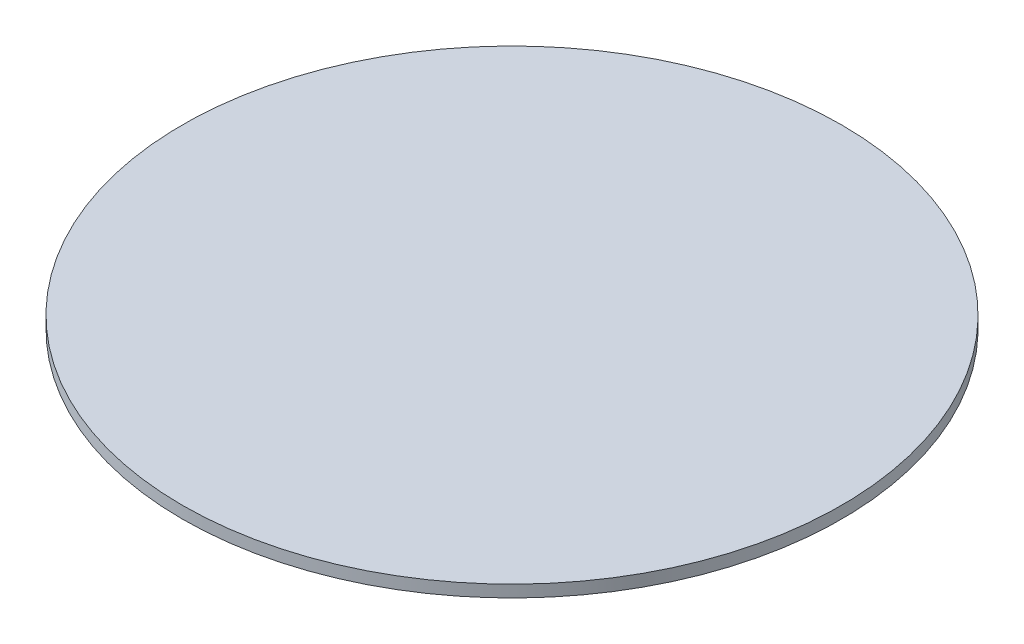
SolidWorks part; units mm, degrees
ref_plane "Front Plane" through (0, 0, 0) normal (0, 0, 1) x (1, 0, 0)
ref_plane "Top Plane" through (0, 0, 0) normal (0, 1, 0) x (1, 0, 0)
ref_plane "Right Plane" through (0, 0, 0) normal (1, 0, 0) x (0, 0, -1)
other "Configuration Table"
sketch "Sketch1" plane through (0, 0, 0) normal (0, 1, 0) x (1, 0, 0)
  circle A0 centre (350, 300) radius 165
extrude "OVEN_tepsi_nisi_halkasi_D330" add sketch "Sketch1" along normal blind 6 from offset 872 separate body
